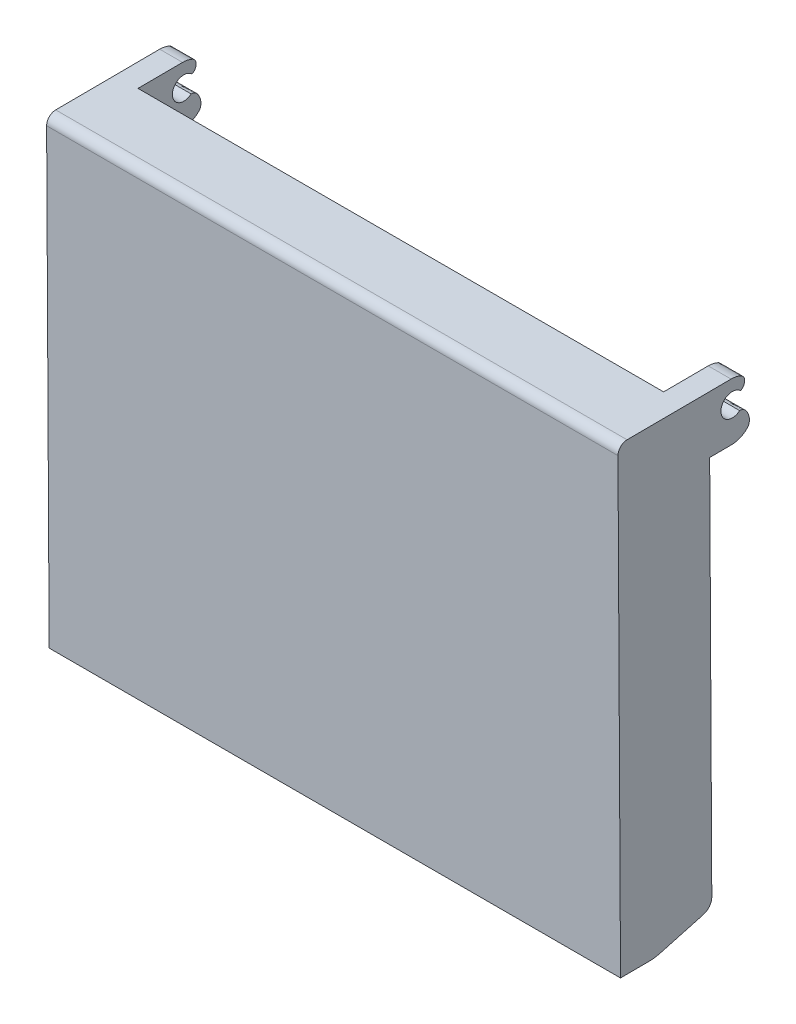
SolidWorks part; units mm, degrees
material "PS HI"
ref_plane "Front Plane" through (0, 0, 0) normal (0, 0, 1) x (1, 0, 0)
ref_plane "Top Plane" through (0, 0, 0) normal (0, 1, 0) x (1, 0, 0)
ref_plane "Right Plane" through (0, 0, 0) normal (1, 0, 0) x (0, 0, -1)
sketch "Sketch1" plane through (0, 0, 0) normal (1, 0, 0) x (0, 0, -1)
  line L0 (-3.8865, 40.6292) -> (-3.8584, 35.6293)
  line L1 (-3.8584, 35.6293) -> (-7.7584, 35.6074)
  line L5 (-7.7584, 35.6074) -> (-7.5708, 2.215)
  line L8 (-8.3065, 1.2449) -> (-12.0509, 0.219)
  line L9 (-13.0854, 0.0769) -> (-15.5588, 0.063)
  line L10 (-15.5588, 0.063) -> (-15.7819, 39.7623)
  line L11 (-14.9864, 40.5668) -> (-3.8865, 40.6292)
  arc A1 (-14.9864, 40.5668) -> (-15.7819, 39.7623) centre (-14.9819, 39.7668) ccw
  arc A2 (-13.0854, 0.0769) -> (-12.0509, 0.219) centre (-13.1079, 4.0768) ccw
  arc A3 (-8.3065, 1.2449) -> (-7.5708, 2.215) centre (-8.5707, 2.2093) ccw
  dimension "D1" = 11.1
extrude "Boss-Extrude1" add sketch "Sketch1" against normal blind 50
sketch "Sketch2" plane through (0, 0, 0) normal (1, 0, 0) x (0, 0, -1)
sketch "Sketch4" plane through (0, 1.3524, -213.9266) normal (0, 1, 0.0056) x (1, 0, 0)
  line L15 (-48, -221.489) -> (-2, -221.489)
  line L16 (-48, -221.489) -> (-48, -213.0677)
  line L17 (-48, -213.0677) -> (-2, -213.0677)
  line L18 (-2, -221.489) -> (-2, -213.0677)
fillet "Fillet5" radius 2 1 edges at (-25, 35.6293, 3.8584)
sketch "Sketch5" plane through (0, 0.1504, 0.0008) normal (0, -1, -0.0056) x (1, 0, 0)
  line L0 (-50, 12.0495) -> (-50, 8.2994) construction
  line L1 (-48, 13.0582) -> (-2, 13.0582)
  line L2 (-48, 13.0582) -> (-48, 7.5582)
  line L3 (-48, 7.5582) -> (-2, 7.5582)
  line L4 (-2, 13.0582) -> (-2, 7.5582)
  line L5 (-50, 15.5582) -> (0, 15.5582) construction
  line L6 (0, 12.0495) -> (0, 8.2994) construction
  dimension "D1" = 2
  dimension "D2" = 2
  dimension "D3" = 2.5
extrude "Cut-Extrude1" cut sketch "Sketch5" against normal up to vertex (35.5 mm away)
sketch "Sketch6" plane through (0, 0, 0) normal (1, 0, 0) x (0, 0, -1)
  line L0 (-3.8697, 37.6292) -> (-3.8865, 40.6292) construction
  line L1 (-3.8865, 40.6292) -> (-14.9864, 40.5668) construction
  circle A0 centre (-5.7753, 38.6185) radius 1
  dimension "D1" = 2
  dimension "D2" = 1.9
  dimension "D3" = 2
extrude "Cut-Extrude2" cut sketch "Sketch6" against normal up to surface (50 mm away) up to face at (-50, 21.2023, 9.845)
fillet "Fillet8" radius 2 1 edges at (-25, 40.6292, 3.8865)
sketch "Sketch7" plane through (0, 0, 0) normal (1, 0, 0) x (0, 0, -1)
  line L2 (-5.5469, 39.5921) -> (-5.5469, 37.645)
  line L6 (-4.4475, 36.2118) -> (-3.7299, 36.2118)
  line L7 (-3.7299, 36.2118) -> (-3.7299, 40.422)
  line L8 (-3.7299, 40.422) -> (-5.0118, 40.422)
  circle A6 centre (-5.7753, 38.6185) radius 1 construction
  arc A7 (-3.8753, 38.6292) -> (-5.8865, 40.618) centre (-5.8753, 38.618) ccw construction
  spline S0 degree 3 poles (-5.5469, 37.645) (-4.7079, 38.4279) (-3.9328, 36.7953) (-4.4475, 36.2118) knots 0 0 0 0 1 1 1 1
  spline S1 degree 3 poles (-5.272, 39.4827) (-5.081, 39.3213) (-4.9543, 39.3484) (-4.5875, 39.7711) (-4.6942, 40.2677) (-5.0118, 40.422) knots 0 0 0 0 0.130865 0.344472 1 1 1 1
  spline S2 degree 2 poles (-5.5469, 39.5921) (-5.4442, 39.5667) (-5.272, 39.4827) knots 0 0 0 1 1 1
  dimension "D1" = 0.2963
extrude "Cut-Extrude3" cut sketch "Sketch7" against normal up to surface (50 mm away) up to face at (-50, 38.6185, 4.7753)
sketch "Sketch9" plane through (0, -0.0874, 15.5579) normal (0, -0.0056, 1) x (1, 0, 0)
  line L0 (-50, 40.6504) -> (0, 40.6504) construction
  line L1 (-48, 40.7363) -> (-2, 40.7363)
  line L2 (-48, 40.7363) -> (-48, 35.6504)
  line L3 (-48, 35.6504) -> (-2, 35.6504)
  line L4 (-2, 40.7363) -> (-2, 35.6504)
  line L5 (-50, 39.8504) -> (-50, 0.1504) construction
  line L6 (0, 39.8504) -> (0, 0.1504) construction
  dimension "D1" = 2
  dimension "D2" = 2
  dimension "D3" = 5
extrude "Cut-Extrude4" cut sketch "Sketch9" against normal up to next from offset 6
